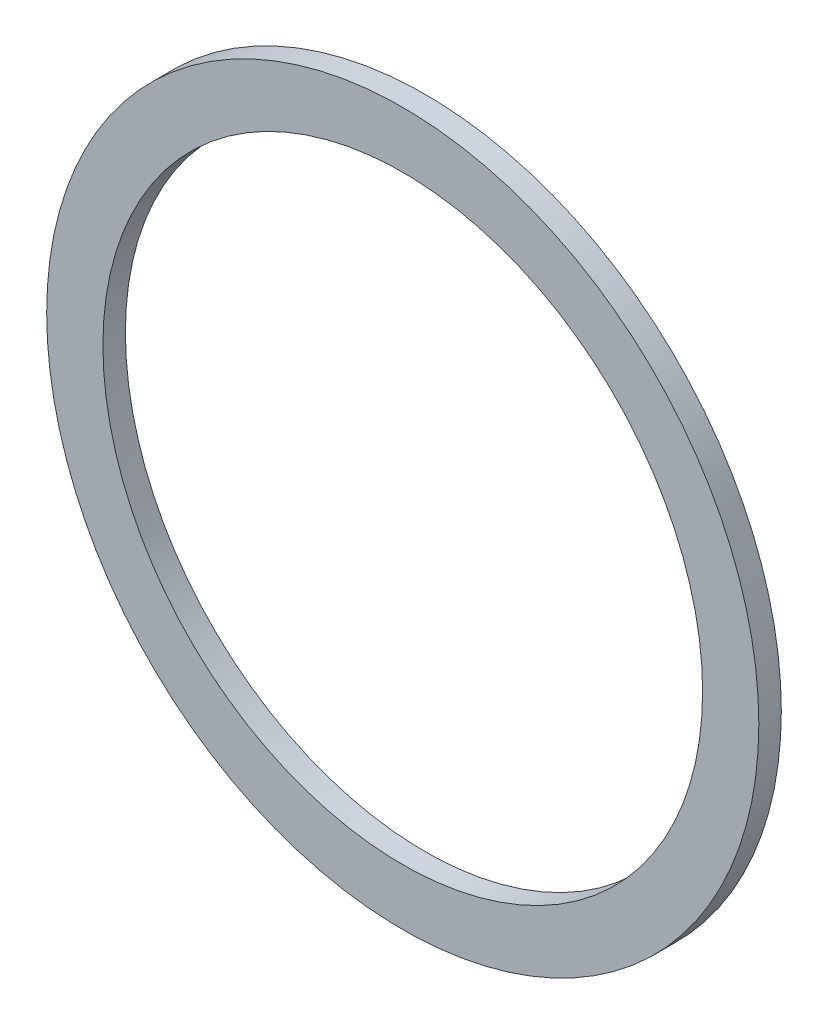
SolidWorks part; units mm, degrees
material "AISI Type 316L stainless steel"
ref_plane "Front Plane" through (0, 0, 0) normal (0, 0, 1) x (1, 0, 0)
ref_plane "Top Plane" through (0, 0, 0) normal (0, 1, 0) x (1, 0, 0)
ref_plane "Right Plane" through (0, 0, 0) normal (1, 0, 0) x (0, 0, -1)
sketch "Extrude sketch 1" plane through (0, 0, 0) normal (0, 0, 1) x (1, 0, 0)
  circle A0 centre (240, 0) radius 95
  circle A1 centre (240, 0) radius 80
  dimension "D1" = 160
  dimension "D2" = 190
extrude "Extrude 1" add sketch "Extrude sketch 1" along normal blind 6 from offset 303 separate body
